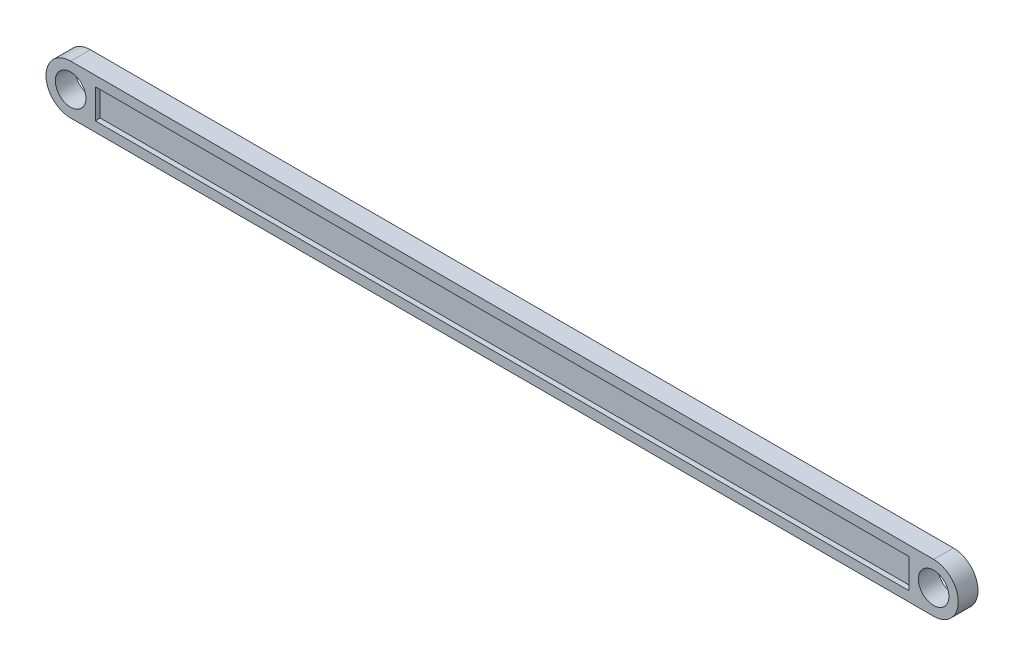
SolidWorks part; units mm, degrees
ref_plane "Alzado" through (0, 0, 0) normal (0, 0, 1) x (1, 0, 0)
ref_plane "Planta" through (0, 0, 0) normal (0, 1, 0) x (1, 0, 0)
ref_plane "Vista lateral" through (0, 0, 0) normal (1, 0, 0) x (0, 0, -1)
sketch "Croquis1" plane through (0, 0, 0) normal (0, 0, 1) x (1, 0, 0)
  line L0 (0, 5) -> (175, 5)
  line L1 (175, -5) -> (0, -5)
  circle A0 centre (0, 0) radius 3.1
  circle A1 centre (175, 0) radius 3.1
  arc A2 (0, 5) -> (0, -5) centre (0, 0) ccw
  arc A3 (175, -5) -> (175, 5) centre (175, 0) ccw
  dimension "D2" = 6.2
  dimension "D3" = 6.2
  dimension "D4" = 10
  dimension "D5" = 10
  dimension "D1" = 175
extrude "Saliente-Extruir1" add sketch "Croquis1" along normal blind 4
sketch "Croquis2" plane through (0, 0, 4) normal (0, 0, 1) x (1, 0, 0)
  line L0 (175, 5) -> (0, 5) construction
  line L1 (5, -3) -> (170, -3)
  line L2 (5, -3) -> (5, 3)
  line L3 (5, 3) -> (170, 3)
  line L4 (170, -3) -> (170, 3)
  line L5 (0, -5) -> (175, -5) construction
  circle A0 centre (175, 0) radius 3.1 construction
  dimension "D1" = 2
  dimension "D2" = 2
  dimension "D3" = 5
  dimension "D4" = 5
extrude "Cortar-Extruir1" cut sketch "Croquis2" against normal blind 1
sketch "Croquis3" plane through (0, 0, 0) normal (0, 0, -1) x (-1, 0, 0)
  line L0 (-175, 5) -> (0, 5) construction
  line L1 (-170, -3) -> (-5, -3)
  line L2 (-170, -3) -> (-170, 3)
  line L3 (-170, 3) -> (-5, 3)
  line L4 (-5, -3) -> (-5, 3)
  line L5 (0, -5) -> (-175, -5) construction
  circle A0 centre (-175, 0) radius 3.1 construction
  dimension "D2" = 5
  dimension "D1" = 5
  dimension "D3" = 2
  dimension "D4" = 2
extrude "Cortar-Extruir2" cut sketch "Croquis3" against normal blind 1
